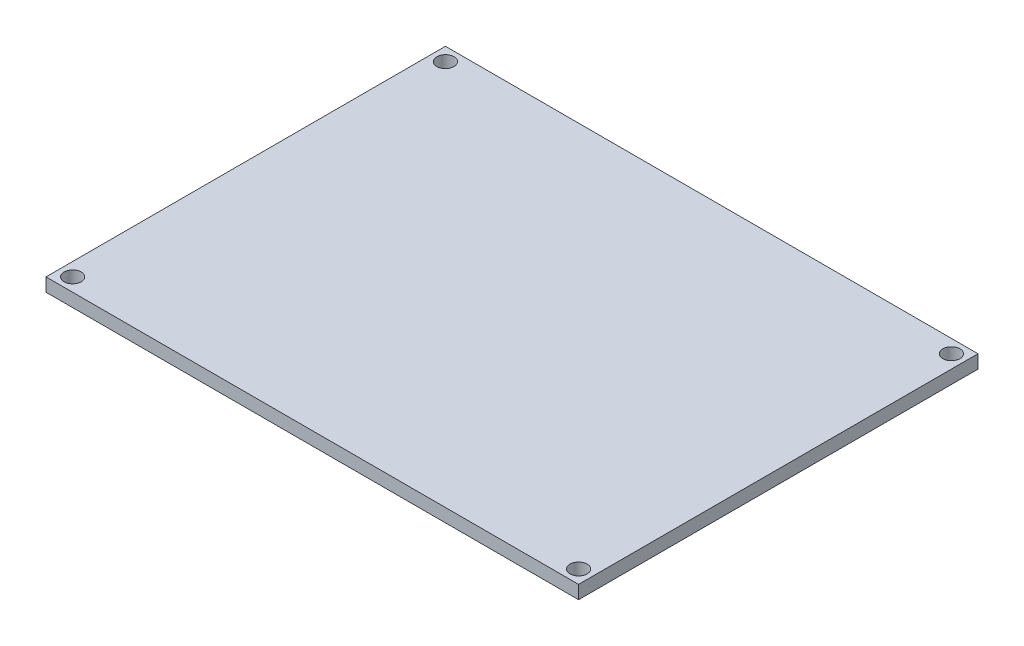
SolidWorks part; units mm, degrees
ref_plane "Front Plane" through (0, 0, 0) normal (0, 0, 1) x (1, 0, 0)
ref_plane "Top Plane" through (0, 0, 0) normal (0, 1, 0) x (1, 0, 0)
ref_plane "Right Plane" through (0, 0, 0) normal (1, 0, 0) x (0, 0, -1)
sketch "Sketch1" plane through (0, 0, 0) normal (0, 1, 0) x (1, 0, 0)
  line L1 (0, 0) -> (101.6, 0)
  line L2 (0, 0) -> (0, 76.2)
  line L3 (0, 76.2) -> (101.6, 76.2)
  line L4 (101.6, 0) -> (101.6, 76.2)
  dimension "D1" = 101.6
  dimension "D2" = 76.2
extrude "Boss-Extrude1" add sketch "Sketch1" along normal blind 2.54
hole_wizard "#4 Clearance Hole1" positions "Sketch3" profile "Sketch2" hole size "#4" standard "ANSI Inch"
sketch "Sketch3" plane through (0, 2.54, 0) normal (0, 1, 0) x (1, 0, 0)
  line L0 (0, 76.2) -> (0, 0) construction
  line L1 (101.6, 76.2) -> (0, 76.2) construction
  line L2 (101.6, 0) -> (101.6, 76.2) construction
  line L3 (0, 0) -> (101.6, 0) construction
  point P0 (2.54, 73.66)
  point P2 (2.54, 2.54)
  point P4 (99.06, 73.66)
  point P6 (99.06, 2.54)
  dimension "D1" = 2.54
  dimension "D2" = 2.54
  dimension "D3" = 2.54
  dimension "D4" = 2.54
sketch "Sketch2" plane through (2.54, 2.54, -73.66) normal (1, 0, 0) x (0, 0, 1)
  line L0 (0, 0) -> (0, 11.1406)
  line L1 (0, 11.1406) -> (1.6319, 10.16)
  line L2 (1.6319, 10.16) -> (1.6319, 0)
  line L5 (1.6319, 0) -> (0, 0)
  line L10 (0, 11.1406) -> (-1.6319, 10.16) construction
  line L11 (0, -6.35) -> (0, 107.95) construction
  dimension "Hole Dia." = 3.2639
  dimension "Hole Depth" = 10.16
  dimension "Drill Angle" = 118
